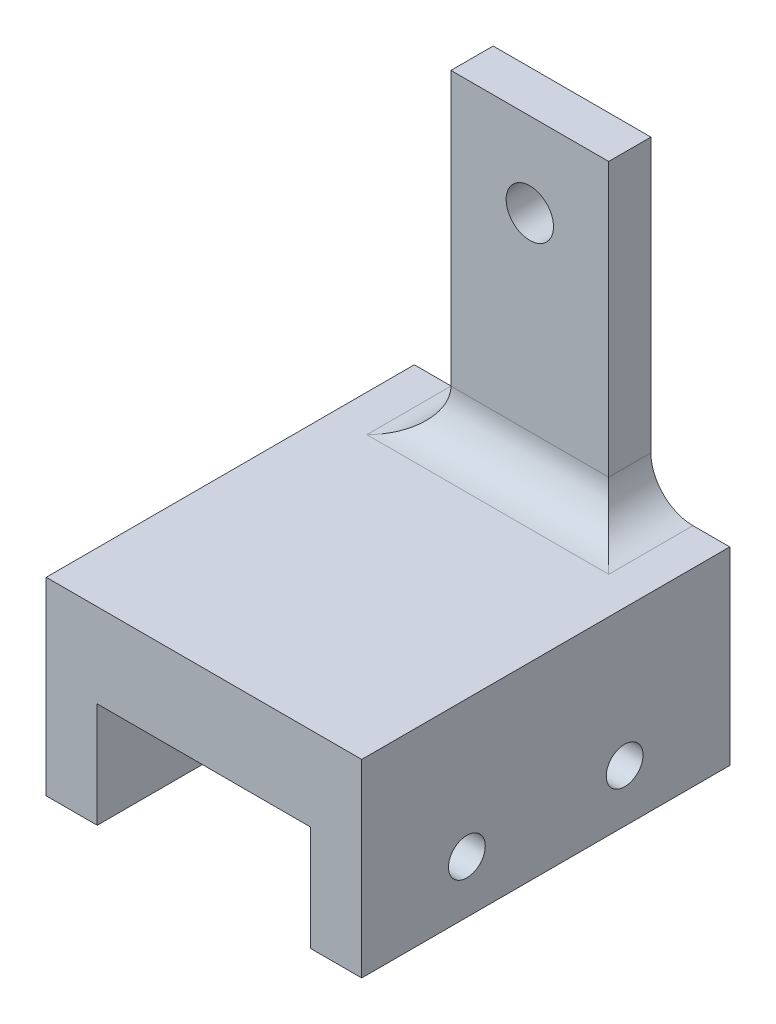
SolidWorks part; units mm, degrees
ref_plane "Alzado" through (0, 0, 0) normal (0, 0, 1) x (1, 0, 0)
ref_plane "Planta" through (0, 0, 0) normal (0, 1, 0) x (1, 0, 0)
ref_plane "Vista lateral" through (0, 0, 0) normal (1, 0, 0) x (0, 0, -1)
sketch "Croquis1" plane through (0, 0, 0) normal (0, 0, 1) x (1, 0, 0)
  line L1 (-15, -15) -> (15, -15)
  line L2 (-15, -15) -> (-15, 15)
  line L3 (-15, 15) -> (15, 15)
  line L4 (15, -15) -> (15, 15)
  line L5 (-15, -15) -> (15, 15) construction
  line L6 (-15, 15) -> (15, -15) construction
  point P0 (0, 0)
  dimension "D1" = 30
  dimension "D2" = 30
extrude "Saliente-Extruir1" add sketch "Croquis1" along normal blind 7
sketch "Croquis2" plane through (0, -15, 0) normal (0, -1, 0) x (1, 0, 0)
  line L1 (15, 0) -> (-15, 0)
  line L2 (15, 0) -> (15, 35)
  line L3 (15, 35) -> (-15, 35)
  line L4 (-15, 0) -> (-15, 35)
  dimension "D1" = 35
extrude "Saliente-Extruir2" add sketch "Croquis2" along normal blind 8
sketch "Croquis3" plane through (0, -23, 0) normal (0, -1, 0) x (-1, 0, 0)
  line L0 (-15, -35) -> (15, -35) construction
  line L1 (15, 0) -> (10.15, 0)
  line L2 (15, 0) -> (15, -35)
  line L3 (15, -35) -> (10.15, -35)
  line L4 (10.15, 0) -> (10.15, -35)
  line L6 (-15, 0) -> (-10.15, 0)
  line L7 (-15, 0) -> (-15, -35)
  line L8 (-15, -35) -> (-10.15, -35)
  line L9 (-10.15, 0) -> (-10.15, -35)
  dimension "D1" = 20.3
  dimension "D2" = 4.85
extrude "Saliente-Extruir3" add sketch "Croquis3" along normal blind 10
sketch "Croquis4" plane through (0, 0, 7) normal (0, 0, 1) x (1, 0, 0)
  line L0 (15, 15) -> (-15, 15) construction
  line L3 (15, -15) -> (15, 15) construction
  circle A0 centre (0, 7) radius 2.25
  dimension "D1" = 4.5
  dimension "D2" = 8
  dimension "D3" = 15
extrude "Cortar-Extruir1" cut sketch "Croquis4" against normal up to next
sketch "Croquis7" plane through (0, 0, 7) normal (0, 0, 1) x (1, 0, 0)
  line L1 (-15, 15) -> (15, 15)
  line L2 (-15, 15) -> (-15, -15)
  line L3 (-15, -15) -> (15, -15)
  line L4 (15, 15) -> (15, -15)
extrude "Cortar-Extruir4" cut sketch "Croquis7" against normal up to next
sketch "Croquis8" plane through (0, -15, 0) normal (0, 1, 0) x (1, 0, 0)
  line L1 (-7.5, 0) -> (7.5, 0)
  line L2 (-7.5, 0) -> (-7.5, -4.016)
  line L3 (-7.5, -4.016) -> (7.5, -4.016)
  line L4 (7.5, 0) -> (7.5, -4.016)
  line L5 (-7.5, 0) -> (7.5, -4.016) construction
  line L6 (-7.5, -4.016) -> (7.5, 0) construction
  line L7 (-15, 0) -> (15, 0) construction
  line L8 (-15, -35) -> (-15, 0) construction
  dimension "D1" = 15
  dimension "D2" = 0
  dimension "D3" = 7.5
extrude "Saliente-Extruir4" add sketch "Croquis8" along normal blind 30
sketch "Croquis9" plane through (0, 0, 4.016) normal (0, 0, 1) x (1, 0, 0)
  line L0 (-7.5, 15) -> (7.5, 15) construction
  line L1 (7.5, 15) -> (7.5, -15) construction
  circle A0 centre (0, 7) radius 2.25
  dimension "D1" = 4.5
  dimension "D3" = 7.5
  dimension "D2" = 8
extrude "Cortar-Extruir5" cut sketch "Croquis9" against normal up to next
fillet "Redondeo3" radius 4 3 edges at (7.5, -15, 2.008) (-7.5, -15, 2.008) (0, -15, 4.016)
sketch "Croquis10" plane through (-10.15, 0, 0) normal (1, 0, 0) x (0, 0, -1)
  line L0 (0, -23) -> (-35, -23) construction
  line L1 (-35, -33) -> (-35, -23) construction
  line L2 (0, -33) -> (0, -23) construction
  circle A0 centre (-10, -28) radius 1.75
  circle A1 centre (-25, -28) radius 1.75
  dimension "D1" = 3.5
  dimension "D3" = 10
  dimension "D4" = 3.5
  dimension "D5" = 5
  dimension "D2" = 5
  dimension "D6" = 10
extrude "Cortar-Extruir6" cut sketch "Croquis10" against normal through all both and the other way through all
